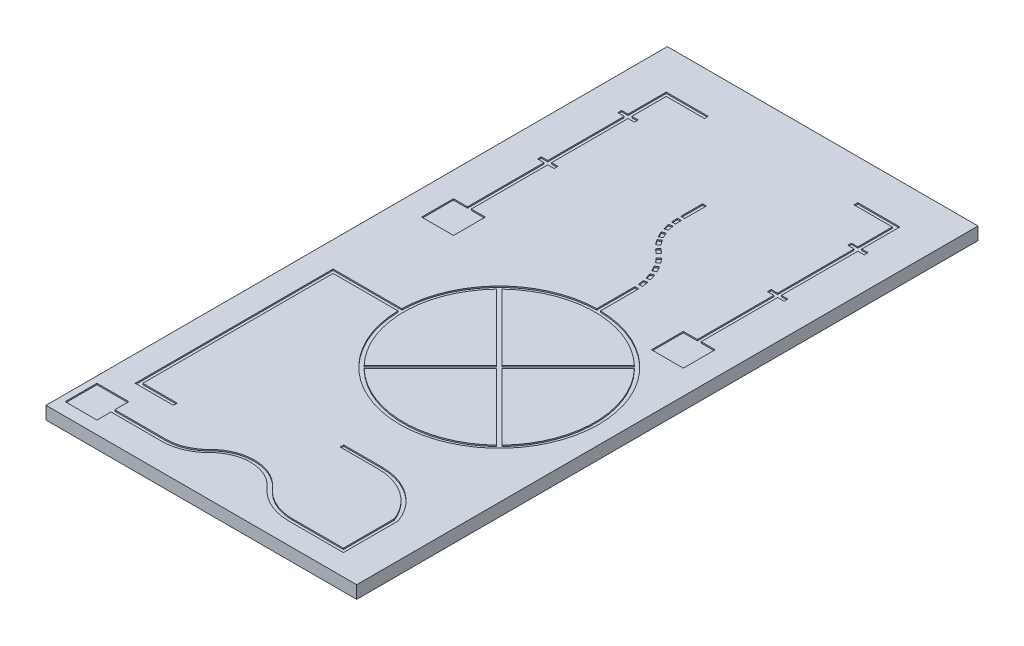
SolidWorks part; units mm, degrees
ref_plane "Front Plane" through (0, 0, 0) normal (0, 0, 1) x (1, 0, 0)
ref_plane "Top Plane" through (0, 0, 0) normal (0, 1, 0) x (1, 0, 0)
ref_plane "Right Plane" through (0, 0, 0) normal (1, 0, 0) x (0, 0, -1)
sketch "Sketch1" plane through (0, 0, 0) normal (0, 1, 0) x (1, 0, 0)
  line L1 (1219.2, -2438.4) -> (-1219.2, -2438.4)
  line L2 (1219.2, -2438.4) -> (1219.2, 2438.4)
  line L3 (1219.2, 2438.4) -> (-1219.2, 2438.4)
  line L4 (-1219.2, -2438.4) -> (-1219.2, 2438.4)
  line L5 (1219.2, -2438.4) -> (-1219.2, 2438.4) construction
  line L6 (1219.2, 2438.4) -> (-1219.2, -2438.4) construction
  point P0 (0, 0)
  dimension "D1" = 4876.8
  dimension "D2" = 2438.4
extrude "Boss-Extrude1" add sketch "Sketch1" along normal blind 100
sketch "Sketch2" plane through (0, 100, 0) normal (0, 1, 0) x (1, 0, 0)
  line L0 (-1219.2, 2438.4) -> (-1219.2, -2438.4) construction
  line L1 (-919.2, -2338.4) -> (-1169.2, -2338.4)
  line L2 (-919.2, -2338.4) -> (-919.2, -2228.4)
  line L3 (-919.2, -2088.4) -> (-1169.2, -2088.4)
  line L4 (-1169.2, -2338.4) -> (-1169.2, -2088.4)
  line L5 (-919.2, -2338.4) -> (-1169.2, -2088.4) construction
  line L6 (-919.2, -2088.4) -> (-1169.2, -2338.4) construction
  line L7 (-1219.2, -2438.4) -> (1219.2, -2438.4) construction
  line L8 (-919.2, -2228.4) -> (-519.2, -2228.4)
  line L9 (-919.2, -2213.4) -> (-874.2776, -2213.4) construction
  line L10 (-919.2, -2198.4) -> (-519.2, -2198.4)
  line L11 (-919.2, -2198.4) -> (-919.2, -2088.4)
  line L12 (518.6973, -2271.9533) -> (948.6973, -2271.9533)
  line L13 (518.6973, -2241.9533) -> (918.6973, -2241.9533)
  line L14 (918.6973, -2241.9533) -> (918.6973, -1841.9533)
  line L15 (948.6973, -2271.9533) -> (948.6973, -1841.9533)
  line L17 (518.6973, -1539.0748) -> (218.6973, -1539.0748)
  line L18 (218.6973, -1539.0748) -> (218.6973, -1567.2032)
  line L19 (218.6973, -1567.2032) -> (518.6973, -1567.2032)
  line L20 (-1019.2, -1938.4) -> (-719.2, -1938.4)
  line L21 (-719.2, -1938.4) -> (-719.2, -1908.4)
  line L22 (-719.2, -1908.4) -> (-989.2, -1908.4)
  line L23 (-989.2, -1908.4) -> (-989.2, -415)
  line L24 (-989.2, -415) -> (-479.8558, -415)
  line L25 (300, -400) -> (-1082.2018, -400) construction
  line L26 (-1019.2, -1938.4) -> (-1019.2, -385)
  line L27 (-1019.2, -385) -> (-479.8558, -385)
  line L28 (300, -400) -> (300, -1150) construction
  line L29 (300, -400) -> (830.3301, -930.3301) construction
  line L30 (819.6179, -940.8301) -> (300, -421.2121)
  line L31 (300, -400) -> (-230.3301, 130.3301) construction
  line L32 (840.8301, -919.6179) -> (321.2121, -400)
  line L33 (300, -400) -> (830.3301, 130.3301) construction
  line L34 (830.3301, 130.3301) -> (-230.3301, -930.3301) construction
  line L35 (-240.8301, -919.6179) -> (278.7879, -400)
  line L36 (840.8301, 119.6179) -> (321.2121, -400)
  line L37 (300, -378.7879) -> (819.6179, 140.8301)
  line L38 (278.7879, -400) -> (-240.8301, 119.6179)
  line L39 (300, -421.2121) -> (-219.6179, -940.8301)
  line L40 (300, -378.7879) -> (-219.6179, 140.8301)
  line L41 (300, -400) -> (300, 350) construction
  line L42 (300, 350) -> (300, 632.1211) construction
  line L43 (285, 379.8558) -> (285, 679.8558)
  line L44 (315, 379.8558) -> (315, 679.8558)
  line L45 (285, 679.8558) -> (315, 679.8558)
  line L47 (283.4854, 707.2433) -> (313.3638, 709.8558)
  line L48 (276.8899, 753.4856) -> (306.3073, 759.3304)
  line L49 (270.3336, 781.5256) -> (299.2927, 789.3304)
  line L50 (255.7416, 825.8982) -> (283.6807, 836.8045)
  line L51 (243.6288, 853.9382) -> (270.7213, 866.8045)
  line L52 (221.3238, 894.9789) -> (246.8572, 910.7139)
  line L53 (202.4819, 923.0189) -> (226.6982, 940.7139)
  line L54 (172.9117, 959.1776) -> (195.0611, 979.4001)
  line L55 (144.8258, 987.2176) -> (165.012, 1009.4001)
  line L57 (104.4289, 1065.1132) -> (81.255, 1046.0708)
  line L58 (77.2262, 1102.6314) -> (51.9232, 1086.5256)
  line L59 (64.2637, 1124.5744) -> (37.9461, 1110.1861)
  line L60 (16.6704, 1155.4) -> (44.5324, 1166.5062)
  line L61 (34.3337, 1195.4) -> (5.6734, 1186.5553)
  line L62 (23.3708, 1240.4268) -> (-6.1476, 1235.1065)
  line L63 (-10.1201, 1262.2983) -> (19.6866, 1265.6449)
  line L64 (-12.6825, 1312.2021) -> (17.3102, 1311.9261)
  line L65 (18.3921, 1337.3888) -> (17.294, 1337.4721)
  line L66 (-12.7, 1337.4721) -> (-12.7, 1508.4)
  line L67 (-12.7, 1508.4) -> (17.294, 1508.4)
  line L68 (17.294, 1508.4) -> (17.294, 1337.4721)
  line L69 (2.297, 1508.4) -> (2.297, 2375.9732) construction
  line L70 (-584.703, 2095.4) -> (-884.703, 2095.4)
  line L71 (-584.703, 2095.4) -> (-584.703, 2125.4)
  line L72 (-584.703, 2125.4) -> (-914.703, 2125.4)
  line L73 (-914.703, 2125.4) -> (-914.703, 1825.4)
  line L75 (-884.703, 1825.4) -> (-884.703, 2095.4)
  line L82 (1219.2, 2438.4) -> (-1219.2, 2438.4) construction
  line L83 (126.2742, 1040.9739) -> (108.6188, 1016.7287)
  line L84 (-914.703, 1795.4) -> (-914.703, 1195.4)
  line L86 (-884.703, 565.4) -> (-884.703, 1165.4)
  line L87 (-884.703, 1825.4) -> (-834.703, 1825.4)
  line L88 (-834.703, 1825.4) -> (-834.703, 1795.4)
  line L89 (-834.703, 1795.4) -> (-884.703, 1795.4)
  line L90 (-884.703, 1195.4) -> (-834.703, 1195.4)
  line L91 (-914.703, 1795.4) -> (-964.703, 1795.4)
  line L92 (-964.703, 1795.4) -> (-964.703, 1825.4)
  line L93 (-964.703, 1825.4) -> (-914.703, 1825.4)
  line L94 (-834.703, 1195.4) -> (-834.703, 1165.4)
  line L95 (-834.703, 1165.4) -> (-884.703, 1165.4)
  line L96 (-899.703, 565.4) -> (-899.703, 505.0509) construction
  line L97 (-914.703, 1165.4) -> (-964.703, 1165.4)
  line L98 (-964.703, 1165.4) -> (-964.703, 1195.4)
  line L99 (-964.703, 1195.4) -> (-914.703, 1195.4)
  line L100 (-884.703, 1195.4) -> (-884.703, 1795.4)
  line L101 (-914.703, 1165.4) -> (-914.703, 565.4)
  line L102 (-884.703, 565.4) -> (-774.703, 565.4)
  line L103 (-774.703, 565.4) -> (-774.703, 315.4)
  line L104 (-774.703, 315.4) -> (-1024.703, 315.4)
  line L105 (-1024.703, 315.4) -> (-1024.703, 565.4)
  line L106 (-1024.703, 565.4) -> (-914.703, 565.4)
  line L107 (17.294, 1337.4721) -> (-12.7, 1337.4721)
  line L108 (17.294, 1311.9263) -> (17.294, 1308.4)
  line L109 (889.297, 565.4) -> (779.297, 565.4)
  line L110 (779.297, 565.4) -> (779.297, 315.4)
  line L111 (779.297, 315.4) -> (1029.297, 315.4)
  line L112 (1029.297, 315.4) -> (1029.297, 565.4)
  line L113 (1029.297, 565.4) -> (919.297, 565.4)
  line L114 (919.297, 1165.4) -> (919.297, 565.4)
  line L115 (919.297, 1165.4) -> (969.297, 1165.4)
  line L116 (969.297, 1165.4) -> (969.297, 1195.4)
  line L117 (969.297, 1195.4) -> (919.297, 1195.4)
  line L118 (919.297, 1795.4) -> (919.297, 1195.4)
  line L119 (919.297, 1795.4) -> (969.297, 1795.4)
  line L120 (969.297, 1795.4) -> (969.297, 1825.4)
  line L121 (969.297, 1825.4) -> (919.297, 1825.4)
  line L122 (919.297, 2125.4) -> (919.297, 1825.4)
  line L123 (589.297, 2125.4) -> (919.297, 2125.4)
  line L124 (589.297, 2095.4) -> (589.297, 2125.4)
  line L125 (589.297, 2095.4) -> (889.297, 2095.4)
  line L126 (889.297, 1825.4) -> (889.297, 2095.4)
  line L127 (889.297, 1825.4) -> (839.297, 1825.4)
  line L128 (839.297, 1825.4) -> (839.297, 1795.4)
  line L129 (839.297, 1795.4) -> (889.297, 1795.4)
  line L130 (889.297, 1195.4) -> (889.297, 1795.4)
  line L131 (889.297, 1195.4) -> (839.297, 1195.4)
  line L132 (839.297, 1195.4) -> (839.297, 1165.4)
  line L133 (839.297, 1165.4) -> (889.297, 1165.4)
  line L134 (889.297, 565.4) -> (889.297, 1165.4)
  arc A0 (-519.2, -2228.4) -> (-256.4254, -2117.5698) centre (-519.2, -1861.47) ccw
  arc A1 (-519.2, -2198.4) -> (-277.9097, -2096.6312) centre (-519.2, -1861.47) ccw
  arc A3 (208.9279, -2130.8016) -> (-256.4254, -2117.5698) centre (-29.8396, -2338.4) ccw
  arc A4 (231.5673, -2111.1176) -> (518.6973, -2241.9533) centre (518.6973, -1861.47) ccw
  arc A5 (208.9279, -2130.8016) -> (518.6973, -2271.9533) centre (518.6973, -1861.47) ccw
  arc A6 (231.5673, -2111.1176) -> (-277.9097, -2096.6312) centre (-29.8396, -2338.4) ccw
  arc A7 (918.6973, -1841.9533) -> (518.6973, -1567.2032) centre (518.6973, -1995.7519) ccw
  arc A8 (948.6973, -1841.9533) -> (518.6973, -1539.0748) centre (518.6973, -1995.7519) ccw
  arc A9 (840.8301, -919.6179) -> (840.8301, 119.6179) centre (300, -400) ccw
  arc A10 (-479.8558, -415) -> (315, 379.8558) centre (300, -400) ccw
  arc A11 (-240.8301, 119.6179) -> (-240.8301, -919.6179) centre (300, -400) ccw
  arc A12 (-219.6179, -940.8301) -> (819.6179, -940.8301) centre (300, -400) ccw
  arc A13 (819.6179, 140.8301) -> (-219.6179, 140.8301) centre (300, -400) ccw
  arc A14 (285, 379.8558) -> (-479.8558, -385) centre (300, -400) ccw
  arc A17 (-12.7, 1308.4) -> (-10.1201, 1262.2983) centre (400.4986, 1308.4) ccw
  arc A18 (17.294, 1308.4) -> (19.6866, 1265.6449) centre (400.4986, 1308.4) ccw
  arc A19 (270.3336, 781.5256) -> (255.7416, 825.8982) centre (-143.9653, 669.8681) ccw
  arc A20 (283.4854, 707.2433) -> (276.8899, 753.4856) centre (-143.9653, 669.8681) ccw
  arc A21 (313.3638, 709.8558) -> (306.3073, 759.3304) centre (-143.9653, 669.8681) ccw
  arc A22 (299.2927, 789.3304) -> (283.6807, 836.8045) centre (-143.9653, 669.8681) ccw
  arc A23 (270.7213, 866.8045) -> (246.8572, 910.7139) centre (-143.9653, 669.8681) ccw
  arc A24 (243.6288, 853.9382) -> (221.3238, 894.9789) centre (-143.9653, 669.8681) ccw
  arc A25 (226.6982, 940.7139) -> (195.0611, 979.4001) centre (-143.9653, 669.8681) ccw
  arc A26 (202.4819, 923.0189) -> (172.9117, 959.1776) centre (-143.9653, 669.8681) ccw
  arc A27 (144.8258, 987.2176) -> (108.6188, 1016.7287) centre (-143.9653, 669.8681) ccw
  arc A28 (165.012, 1009.4001) -> (126.2742, 1040.9739) centre (-143.9653, 669.8681) ccw
  arc A29 (51.9232, 1086.5256) -> (81.255, 1046.0708) centre (400.4986, 1308.4) ccw
  arc A30 (77.2262, 1102.6314) -> (104.4289, 1065.1132) centre (400.4986, 1308.4) ccw
  arc A31 (44.5324, 1166.5062) -> (64.2637, 1124.5744) centre (400.4986, 1308.4) ccw
  arc A32 (16.6704, 1155.4) -> (37.9461, 1110.1861) centre (400.4986, 1308.4) ccw
  arc A33 (23.3708, 1240.4268) -> (34.3337, 1195.4) centre (400.4986, 1308.4) ccw
  arc A34 (-6.1476, 1235.1065) -> (5.6734, 1186.5553) centre (400.4986, 1308.4) ccw
  arc A35 (17.3102, 1311.9261) -> (19.6866, 1265.6449) centre (400.4986, 1308.4) ccw
  arc A36 (-12.6825, 1312.2021) -> (-10.1201, 1262.2983) centre (400.4986, 1308.4) ccw
  arc A38 (77.2262, 1102.6314) -> (104.4289, 1065.1132) centre (400.4986, 1308.4) ccw
  arc A39 (51.9232, 1086.5256) -> (81.255, 1046.0708) centre (400.4986, 1308.4) ccw
  arc A40 (44.5324, 1166.5062) -> (64.2637, 1124.5744) centre (400.4986, 1308.4) ccw
  arc A41 (16.6704, 1155.4) -> (37.9461, 1110.1861) centre (400.4986, 1308.4) ccw
  arc A42 (23.3708, 1240.4268) -> (34.3337, 1195.4) centre (400.4986, 1308.4) ccw
  arc A43 (-6.1476, 1235.1065) -> (5.6734, 1186.5553) centre (400.4986, 1308.4) ccw
  point P0 (-1044.2, -2213.4)
  point P9 (-1044.2, -2338.4)
  dimension "D9" = 673.8601
  dimension "D10" = 733.8601
  dimension "D11" = 632.794
  dimension "D12" = 489.3604
  dimension "D13" = 760.9667
  dimension "D15" = 30
  dimension "D21" = 857.0975
  dimension "D28" = 1500
  dimension "D31" = 1560
  dimension "D1" = 250
  dimension "D2" = 250
  dimension "D3" = 50
  dimension "D4" = 100
  dimension "D5" = 400
  dimension "D6" = 15
  dimension "D7" = 15
  dimension "D8" = 125
  dimension "D14" = 1037.8973
  dimension "D16" = 30
  dimension "D17" = 30
  dimension "D18" = 400
  dimension "D19" = 430
  dimension "D20" = 400
  dimension "D22" = 400
  dimension "D23" = 300
  dimension "D24" = 300
  dimension "D25" = 270
  dimension "D26" = 30
  dimension "D27" = 150
  dimension "D29" = 300
  dimension "D30" = 400
  dimension "D32" = 15
  dimension "D33" = 15
  dimension "D34" = 100
  dimension "D35" = 45
  dimension "D36" = 15
  dimension "D37" = 45
  dimension "D38" = 15
  dimension "D39" = 15
  dimension "D40" = 15
  dimension "D41" = 1499.7
  dimension "D42" = 519.6179
  dimension "D43" = 45
  dimension "D44" = 15
  dimension "D45" = 15
  dimension "D46" = 15
  dimension "D47" = 15
  dimension "D48" = 1499.7
  dimension "D49" = 15
  dimension "D50" = 15
  dimension "D51" = 300
  dimension "D52" = 30
  dimension "D53" = 50
  dimension "D54" = 30
  dimension "D55" = 50
  dimension "D56" = 30
  dimension "D57" = 50
  dimension "D58" = 30
  dimension "D59" = 50
  dimension "D60" = 30
  dimension "D61" = 50
  dimension "D62" = 1206.5
  dimension "D63" = 50
  dimension "D64" = 40
  dimension "D65" = 50
  dimension "D66" = 40
  dimension "D67" = 50
  dimension "D68" = 40
  dimension "D69" = 50
  dimension "D70" = 40
  dimension "D71" = 200
  dimension "D72" = 29.994
  dimension "D73" = 587
  dimension "D74" = 30
  dimension "D75" = 587
  dimension "D76" = 300
  dimension "D77" = 30
  dimension "D78" = 930
  dimension "D79" = 300
  dimension "D80" = 1260
  dimension "D81" = 30
  dimension "D82" = 50
  dimension "D83" = 50
  dimension "D84" = 330
  dimension "D85" = 30
  dimension "D86" = 887
  dimension "D87" = 30
  dimension "D88" = 30
  dimension "D89" = 50
  dimension "D90" = 50
  dimension "D91" = 600
  dimension "D92" = 30
  dimension "D93" = 600
  dimension "D94" = 125
  dimension "D95" = 125
  dimension "D96" = 250
  dimension "D97" = 110
extrude "Cut-Extrude1" cut sketch "Sketch2" against normal blind 10 contours L15 A8 L17 L18 L19 A7 L14 L13 A4 A6 A1 L10 L11 L3 L4 L1 L2 L8 A0 A3 A5 L12 | L43 A14 L27 L26 L20 L21 L22 L23 L24 A10 L44 L45 A9 L32 L36 A11 L38 L35 A12 L39 L30 A13 L37 L40 | L47 A21 L48 A20 | L49 A22 L50 A19 | A24 L51 A23 L52 | A26 L53 A25 L54 | L55 A28 L83 A27 | A30 L58 A29 L57 | L60 A32 L59 A31 | L62 A34 L61 A33 | L64 A36 A17 L63 A18 L108 | L107 L68 L67 L66 | L134 L109 L110 L111 L112 L113 L114 L115 L116 L117 L118 L119 L120 L121 L122 L123 L124 L125 L126 L127 L128 L129 L130 L131 L132 L133 | L106 L105 L104 L103 L102 L86 L95 L94 L90 L100 L89 L88 L87 L75 L70 L71 L72 L73 L93 L92 L91 L84 L99 L98 L97 L101
